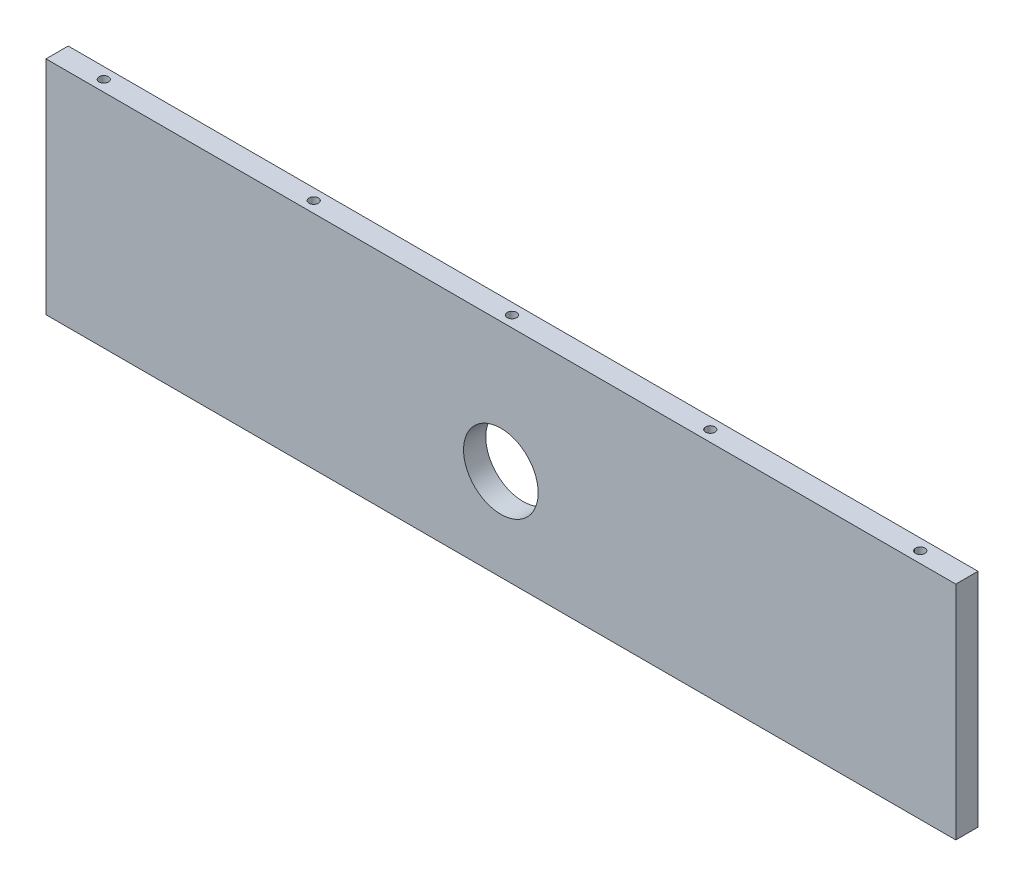
SolidWorks part; units mm, degrees
ref_plane "Plano frontal" through (0, 0, 0) normal (0, 0, 1) x (1, 0, 0)
ref_plane "Plano superior" through (0, 0, 0) normal (0, 1, 0) x (1, 0, 0)
ref_plane "Plano direito" through (0, 0, 0) normal (1, 0, 0) x (0, 0, -1)
sketch "Esboço1" plane through (0, 0, 0) normal (0, 0, 1) x (1, 0, 0)
  line L0 (195, 47.5) -> (-195, -47.5) construction
  line L1 (-195, 47.5) -> (195, 47.5)
  line L2 (-195, 47.5) -> (-195, -47.5)
  line L3 (-195, -47.5) -> (195, -47.5)
  line L4 (195, 47.5) -> (195, -47.5)
  dimension "D1" = 390
  dimension "D2" = 95
extrude "Ressalto-extrusão1" add sketch "Esboço1" along normal blind 9.525
sketch "Esboço3" plane through (0, 0, 9.525) normal (0, 0, 1) x (1, 0, 0)
  line L0 (0, 47.5) -> (0, -47.5) construction
  line L1 (195, 47.5) -> (-195, 47.5) construction
  line L2 (-195, -47.5) -> (195, -47.5) construction
  circle A0 centre (-0.012, -8.12) radius 16
  dimension "D1" = 32
  dimension "D2" = 55.62
extrude "Circulo de rolamento" cut sketch "Esboço3" against normal up to surface (9.525 mm away) up to face at (0, 0, 0)
sketch "Esboço4" plane through (0, 47.5, 0) normal (0, 1, 0) x (1, 0, 0)
  line L0 (-195, -4.7625) -> (195, -4.7625) construction
  line L1 (-195, -9.525) -> (-195, 0) construction
  line L2 (195, -9.525) -> (195, 0) construction
  line L3 (0, 0) -> (0, -9.525) construction
  line L4 (195, 0) -> (-195, 0) construction
  line L5 (195, -9.525) -> (-195, -9.525) construction
  circle A0 centre (175, -4.7625) radius 2
  circle A1 centre (85, -4.7625) radius 2
  circle A2 centre (0, -4.7625) radius 2
  circle A3 centre (-175, -4.7625) radius 2
  circle A4 centre (-85, -4.7625) radius 2
  dimension "D1" = 4
  dimension "D3" = 4
  dimension "D5" = 4
  dimension "D2" = 20
  dimension "D4" = 110
extrude "Corte-extrusão3" cut sketch "Esboço4" against normal blind 20
sketch "Esboço5" plane through (0, -47.5, 0) normal (0, -1, 0) x (1, 0, 0)
  line L0 (-195, 4.7625) -> (195, 4.7625) construction
  line L1 (-195, 9.525) -> (-195, 0) construction
  line L2 (195, 9.525) -> (195, 0) construction
  circle A0 centre (0, 4.7625) radius 2
  circle A1 centre (-115, 4.7625) radius 2
  circle A2 centre (115, 4.7625) radius 2
  dimension "D1" = 4
  dimension "D2" = 4
  dimension "D3" = 4
  dimension "D4" = 80
  dimension "D5" = 80
extrude "Corte-extrusão4" cut sketch "Esboço5" against normal blind 20
